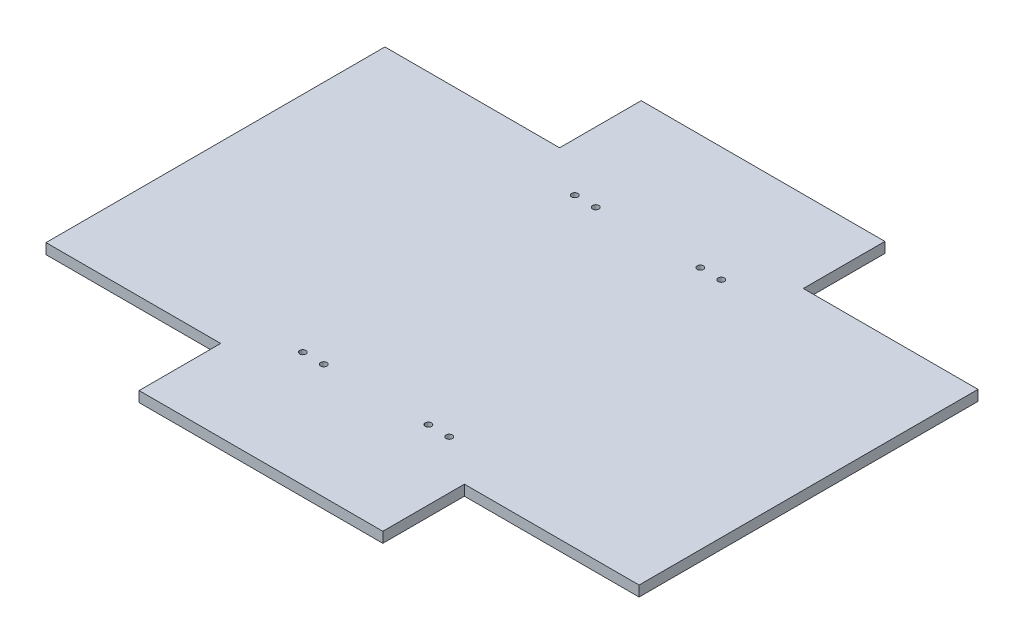
SolidWorks part; units mm, degrees
ref_plane "Front Plane" through (0, 0, 0) normal (0, 0, 1) x (1, 0, 0)
ref_plane "Top Plane" through (0, 0, 0) normal (0, 1, 0) x (1, 0, 0)
ref_plane "Right Plane" through (0, 0, 0) normal (1, 0, 0) x (0, 0, -1)
sketch "Sketch1" plane through (0, 0, 0) normal (0, 1, 0) x (1, 0, 0)
  line L0 (-58.25, 125) -> (58.25, 125)
  line L6 (-147.75, -125) -> (-147.75, 125) construction
  line L7 (-147.75, 125) -> (147.75, 125) construction
  line L8 (147.75, -125) -> (147.75, 125) construction
  line L9 (-147.75, -125) -> (147.75, 125) construction
  line L10 (-147.75, 125) -> (147.75, -125) construction
  line L11 (147.75, -81) -> (147.75, 81)
  line L12 (147.75, 81) -> (58.25, 81)
  line L13 (58.25, 81) -> (58.25, 125)
  line L14 (-15.8128, 0) -> (22.4682, 0) construction
  line L15 (0, 17.3156) -> (0, -20.1679) construction
  line L16 (-58.25, 81) -> (-58.25, 125)
  line L17 (-147.75, 81) -> (-58.25, 81)
  line L18 (-147.75, -81) -> (-147.75, 81)
  line L19 (-147.75, -125) -> (147.75, -125) construction
  line L20 (-147.75, -81) -> (-58.25, -81)
  line L21 (-58.25, -81) -> (-58.25, -125)
  line L22 (58.25, -81) -> (58.25, -125)
  line L23 (147.75, -81) -> (58.25, -81)
  line L24 (-58.25, -125) -> (58.25, -125)
  point P0 (0, 0)
  point P21 (0, 125)
  point P22 (-147.75, 0)
  point P27 (147.75, 0)
  dimension "D1" = 250
  dimension "D2" = 295.5
  dimension "D3" = 44
  dimension "D4" = 89.5
extrude "Boss-Extrude1" add sketch "Sketch1" along normal blind 5
sketch "Sketch2" plane through (0, 0, 0) normal (0, -1, 0) x (1, 0, 0)
  line L0 (-147.75, 81) -> (-147.75, 65) construction
  line L2 (-147.75, -81) -> (-147.75, 81) construction
  line L3 (-147.75, 65) -> (-58.25, 65) construction
  line L4 (147.75, 81) -> (147.75, -81) construction
  line L5 (147.75, 65) -> (147.75, 81) construction
  line L6 (-58.25, 81) -> (-147.75, 81) construction
  line L7 (-58.25, 81) -> (-58.25, 65) construction
  line L8 (-103, 65) -> (-82.5, 65)
  line L9 (-82.5, 65) -> (-82.5, 70)
  line L10 (-82.5, 70) -> (-123.5, 70)
  line L11 (-123.5, 70) -> (-123.5, 65)
  line L12 (-123.5, 65) -> (-103, 65)
  line L13 (-8.2841, 0) -> (10.2958, 0) construction
  line L14 (0, 9.4619) -> (0, -7.0325) construction
  line L15 (123.5, 70) -> (123.5, 65)
  line L16 (82.5, 70) -> (123.5, 70)
  line L17 (82.5, 65) -> (82.5, 70)
  line L18 (103, 65) -> (82.5, 65)
  line L19 (123.5, 65) -> (103, 65)
  line L20 (-123.5, -70) -> (-123.5, -65)
  line L21 (-82.5, -70) -> (-123.5, -70)
  line L22 (-82.5, -65) -> (-82.5, -70)
  line L23 (-103, -65) -> (-82.5, -65)
  line L24 (-123.5, -65) -> (-103, -65)
  line L25 (82.5, -70) -> (123.5, -70)
  line L26 (82.5, -65) -> (82.5, -70)
  line L27 (103, -65) -> (82.5, -65)
  line L28 (123.5, -65) -> (103, -65)
  line L29 (123.5, -70) -> (123.5, -65)
extrude "Cut-Extrude1" cut sketch "Sketch2" against normal blind 0.1
sketch "Sketch3" plane through (0, 5, 0) normal (0, 1, 0) x (1, 0, 0)
  line L0 (-147.75, 81) -> (-141.75, 81)
  line L1 (-147.75, 81) -> (-58.25, 81) construction
  line L2 (-141.75, 81) -> (-141.75, -81)
  line L3 (-147.75, -81) -> (-58.25, -81) construction
  line L4 (-141.75, -81) -> (-147.75, -81)
  line L5 (-147.75, -81) -> (-147.75, 81)
  line L6 (0, -2.75) -> (0, 2.75) construction
  line L7 (141.75, -81) -> (147.75, -81)
  line L8 (141.75, 81) -> (141.75, -81)
  line L9 (147.75, 81) -> (141.75, 81)
  line L10 (147.75, -81) -> (147.75, 81)
  line L11 (-58.25, 125) -> (-58.25, 120)
  line L12 (-58.25, 81) -> (-58.25, 125) construction
  line L13 (-58.25, 120) -> (58.25, 120)
  line L14 (58.25, 81) -> (58.25, 125) construction
  line L15 (58.25, 120) -> (58.25, 125)
  line L16 (58.25, 125) -> (-58.25, 125)
  line L17 (-58.25, -125) -> (58.25, -125)
  line L18 (58.25, -125) -> (58.25, -120)
  line L19 (58.25, -81) -> (58.25, -125) construction
  line L20 (58.25, -120) -> (-58.25, -120)
  line L21 (-58.25, -81) -> (-58.25, -125) construction
  line L22 (-58.25, -120) -> (-58.25, -125)
extrude "Cut-Extrude2" cut sketch "Sketch3" against normal through all both and the other way through all
sketch "Sketch4" [suppressed] plane through (0, 5, 0) normal (0, 1, 0) x (1, 0, 0)
  line L0 (-141.75, 0) -> (141.75, 0) construction
  line L1 (-141.75, 81) -> (-141.75, -81) construction
  line L2 (141.75, -81) -> (141.75, 81) construction
  line L3 (-103, 65) -> (-103, 0) construction
  line L4 (-82.5, 65) -> (-123.5, 65) construction
  line L5 (0, -2.75) -> (0, 2.75) construction
  line L6 (-110.5, 5) -> (-95.5, 5)
  line L7 (-110.5, 5) -> (-110.5, -5)
  line L8 (-110.5, -5) -> (-95.5, -5)
  line L9 (-95.5, 5) -> (-95.5, -5)
  line L10 (-110.5, 5) -> (-95.5, -5) construction
  line L11 (-110.5, -5) -> (-95.5, 5) construction
  line L12 (110.5, -5) -> (95.5, -5)
  line L13 (95.5, 5) -> (95.5, -5)
  line L14 (110.5, 5) -> (95.5, 5)
  line L15 (110.5, 5) -> (110.5, -5)
extrude "Cut-Extrude3" [suppressed] cut sketch "Sketch4" against normal through all both and the other way through all
sketch "Sketch7" plane through (0, 5, 0) normal (0, 1, 0) x (1, 0, 0)
  line L0 (20, -81) -> (40, -81) construction
  line L3 (30, -81) -> (40, -81) construction
  line L7 (20, -81) -> (30, -81) construction
  line L10 (-2.75, 0) -> (2.75, 0) construction
  line L12 (0, -81) -> (58.25, -81) construction
  circle A9 centre (25, -65) radius 1.5
  circle A10 centre (35, -65) radius 1.5
  circle A11 centre (-35, -65) radius 1.5
  circle A12 centre (-25, -65) radius 1.5
  circle A13 centre (-25, 65) radius 1.5
  circle A14 centre (-35, 65) radius 1.5
  circle A15 centre (35, 65) radius 1.5
  circle A16 centre (25, 65) radius 1.5
  dimension "D1" = 20
extrude "Cut-Extrude4" cut sketch "Sketch7" against normal through all both
sketch "Sketch9" plane through (0, 5, 0) normal (0, 1, 0) x (1, 0, 0)
  line L1 (-123.5, 70) -> (-82.5, 70) construction
  line L2 (-123.5, 70) -> (-123.5, 65) construction
  line L3 (-123.5, 65) -> (-82.5, 65) construction
  line L4 (-82.5, 70) -> (-82.5, 65) construction
  line L5 (82.5, 70) -> (123.5, 70) construction
  line L6 (82.5, 70) -> (82.5, 65) construction
  line L7 (82.5, 65) -> (123.5, 65) construction
  line L8 (123.5, 70) -> (123.5, 65) construction
  line L9 (-123.5, -65) -> (-82.5, -65) construction
  line L10 (-123.5, -65) -> (-123.5, -70) construction
  line L11 (-123.5, -70) -> (-82.5, -70) construction
  line L12 (-82.5, -65) -> (-82.5, -70) construction
  line L13 (82.5, -65) -> (123.5, -65) construction
  line L14 (82.5, -65) -> (82.5, -70) construction
  line L15 (82.5, -70) -> (123.5, -70) construction
  line L16 (123.5, -65) -> (123.5, -70) construction
